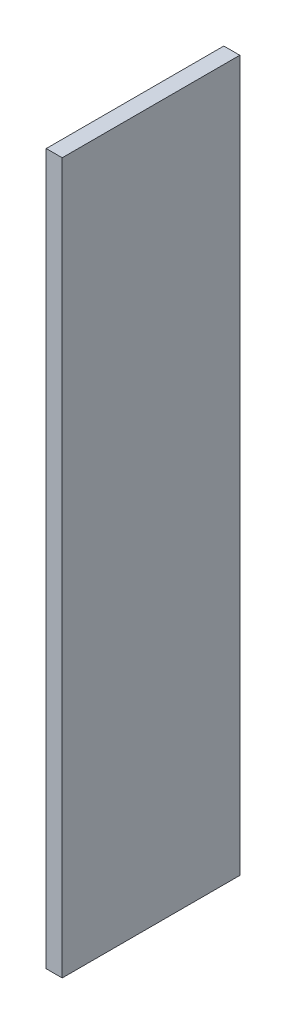
SolidWorks part; units mm, degrees
material "Sosna"
ref_plane "Płaszczyzna przednia" through (0, 0, 0) normal (0, 0, 1) x (1, 0, 0)
ref_plane "Płaszczyzna górna" through (0, 0, 0) normal (0, 1, 0) x (1, 0, 0)
ref_plane "Płaszczyzna prawa" through (0, 0, 0) normal (1, 0, 0) x (0, 0, -1)
sketch "Szkic1" plane through (0, 0, 0) normal (1, 0, 0) x (0, 0, -1)
  line L1 (0, 0) -> (200, 0)
  line L2 (0, 0) -> (0, 800)
  line L3 (0, 800) -> (200, 800)
  line L4 (200, 0) -> (200, 800)
  dimension "D1" = 200
  dimension "D2" = 800
extrude "Dodanie-wyciągnięcie1" add sketch "Szkic1" along normal blind 18
